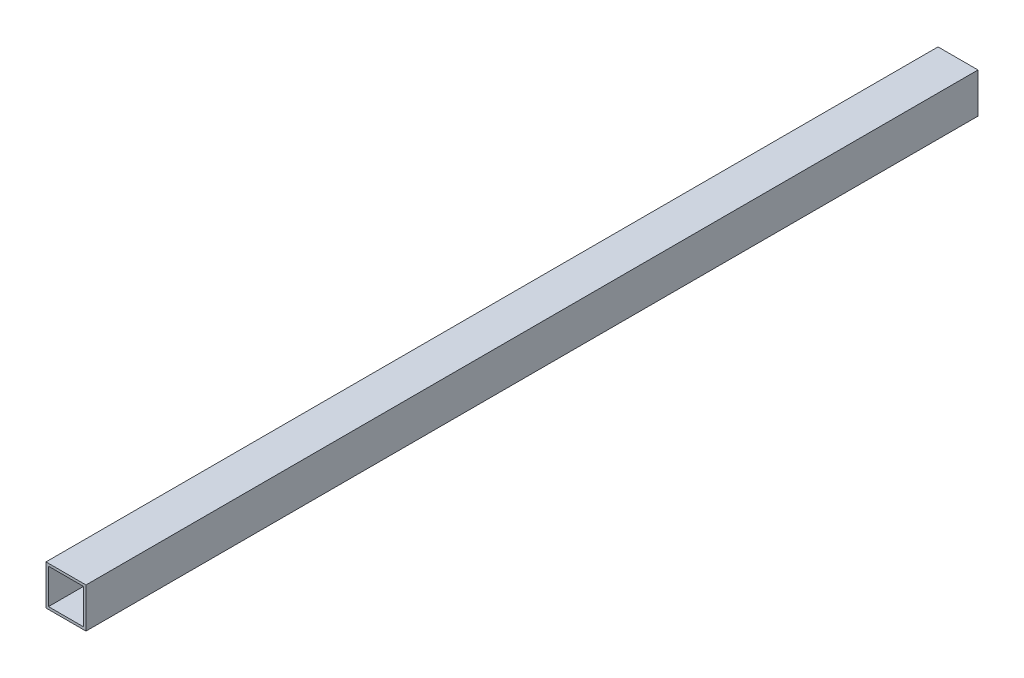
SolidWorks part; units mm, degrees
ref_plane "Alzado" through (0, 0, 0) normal (0, 0, 1) x (1, 0, 0)
ref_plane "Planta" through (0, 0, 0) normal (0, 1, 0) x (1, 0, 0)
ref_plane "Vista lateral" through (0, 0, 0) normal (1, 0, 0) x (0, 0, -1)
sketch "Croquis2" plane through (0, 0, 0) normal (0, 0, 1) x (1, 0, 0)
  line L0 (4.7625, -4.7625) -> (71.4375, -4.7625)
  line L1 (0, 0) -> (76.2, 0)
  line L2 (0, 0) -> (0, -76.2)
  line L3 (0, -76.2) -> (76.2, -76.2)
  line L4 (76.2, 0) -> (76.2, -76.2)
  line L5 (71.4375, -4.7625) -> (71.4375, -71.4375)
  line L6 (4.7625, -71.4375) -> (71.4375, -71.4375)
  line L7 (4.7625, -4.7625) -> (4.7625, -71.4375)
  dimension "D1" = 76.2
  dimension "D2" = 76.2
  dimension "D3" = 4.7625
extrude "Saliente-Extruir1" add sketch "Croquis2" against normal blind 1700
